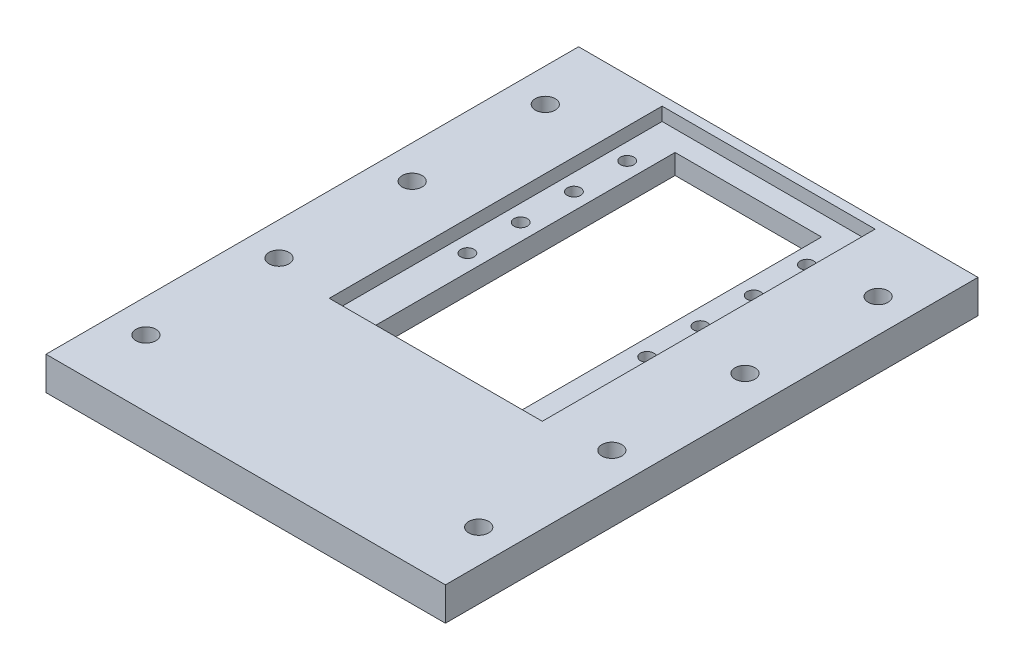
SolidWorks part; units mm, degrees
ref_plane "Front Plane" through (0, 0, 0) normal (0, 0, 1) x (1, 0, 0)
ref_plane "Top Plane" through (0, 0, 0) normal (0, 1, 0) x (1, 0, 0)
ref_plane "Right Plane" through (0, 0, 0) normal (1, 0, 0) x (0, 0, -1)
sketch "Sketch3" plane through (0, 0, 0) normal (0, 1, 0) x (1, 0, 0)
  line L0 (-13.5, 22.8) -> (-13.5, 14.8) construction
  line L1 (13.5, 22.8) -> (13.5, 14.8) construction
  line L2 (-13.5, 22.8) -> (-13.5, 30.8) construction
  line L4 (-30, 40) -> (30, 40)
  line L5 (-30, 40) -> (-30, -40)
  line L6 (-30, -40) -> (30, -40)
  line L7 (30, 40) -> (30, -40)
  line L8 (-30, 40) -> (30, -40) construction
  line L9 (-30, -40) -> (30, 40) construction
  line L11 (-11, 35.5) -> (11, 35.5)
  line L12 (-11, 35.5) -> (-11, -9.5)
  line L13 (-11, -9.5) -> (11, -9.5)
  line L14 (11, 35.5) -> (11, -9.5)
  line L15 (-11, 35.5) -> (11, -9.5) construction
  line L16 (-11, -9.5) -> (11, 35.5) construction
  circle A0 centre (-13.5, 22.8) radius 1
  circle A1 centre (13.5, 22.8) radius 1
  circle A2 centre (-13.5, 14.8) radius 1
  circle A3 centre (-13.5, 6.8) radius 1
  circle A4 centre (13.5, 14.8) radius 1
  circle A5 centre (13.5, 6.8) radius 1
  circle A6 centre (-13.5, 30.8) radius 1
  circle A7 centre (13.5, 30.8) radius 1
  circle A18 centre (0, 0) radius 13 construction
  circle A20 centre (0, 0) radius 9 construction
  circle A21 centre (-25, 30) radius 1.5
  circle A22 centre (25, 30) radius 1.5
  circle A23 centre (-25, 10) radius 1.5
  circle A24 centre (-25, -10) radius 1.5
  circle A25 centre (-25, -30) radius 1.5
  circle A26 centre (25, 10) radius 1.5
  circle A27 centre (25, -10) radius 1.5
  circle A28 centre (25, -30) radius 1.5
  point P12 (0, 0)
  point P27 (0, 13)
  dimension "D1" = 2
  dimension "D11" = 80
  dimension "D12" = 6.8
  dimension "D14" = 3
  dimension "D15" = 26
  dimension "D13" = 18
  dimension "D2" = 27
  dimension "D3" = 13.5
  dimension "D4" = 60
  dimension "D6" = 8
  dimension "D8" = 8
  dimension "D10" = 8
  dimension "D16" = 45
  dimension "D17" = 22
  dimension "D18" = 50
  dimension "D19" = 5
  dimension "D20" = 10
  dimension "D22" = 20
  dimension "D24" = 20
  dimension "D5" = 3
  dimension "D7" = 3
  dimension "D9" = 2
  dimension "D21" = 4
  dimension "D23" = 4
extrude "Boss-Extrude1" add sketch "Sketch3" along normal blind 5
sketch "Sketch4" plane through (0, 5, 0) normal (0, 1, 0) x (1, 0, 0)
  line L1 (-16, 38.55) -> (16, 38.55)
  line L2 (-16, 38.55) -> (-16, -11.45)
  line L3 (-16, -11.45) -> (16, -11.45)
  line L4 (16, 38.55) -> (16, -11.45)
  line L5 (-16, 38.55) -> (16, -11.45) construction
  line L6 (-16, -11.45) -> (16, 38.55) construction
  circle A0 centre (13.5, 30.8) radius 1 construction
  point P0 (0, 13.55)
  dimension "D3" = 7.75
  dimension "D1" = 50
  dimension "D2" = 32
extrude "Cut-Extrude1" cut sketch "Sketch4" against normal blind 2
